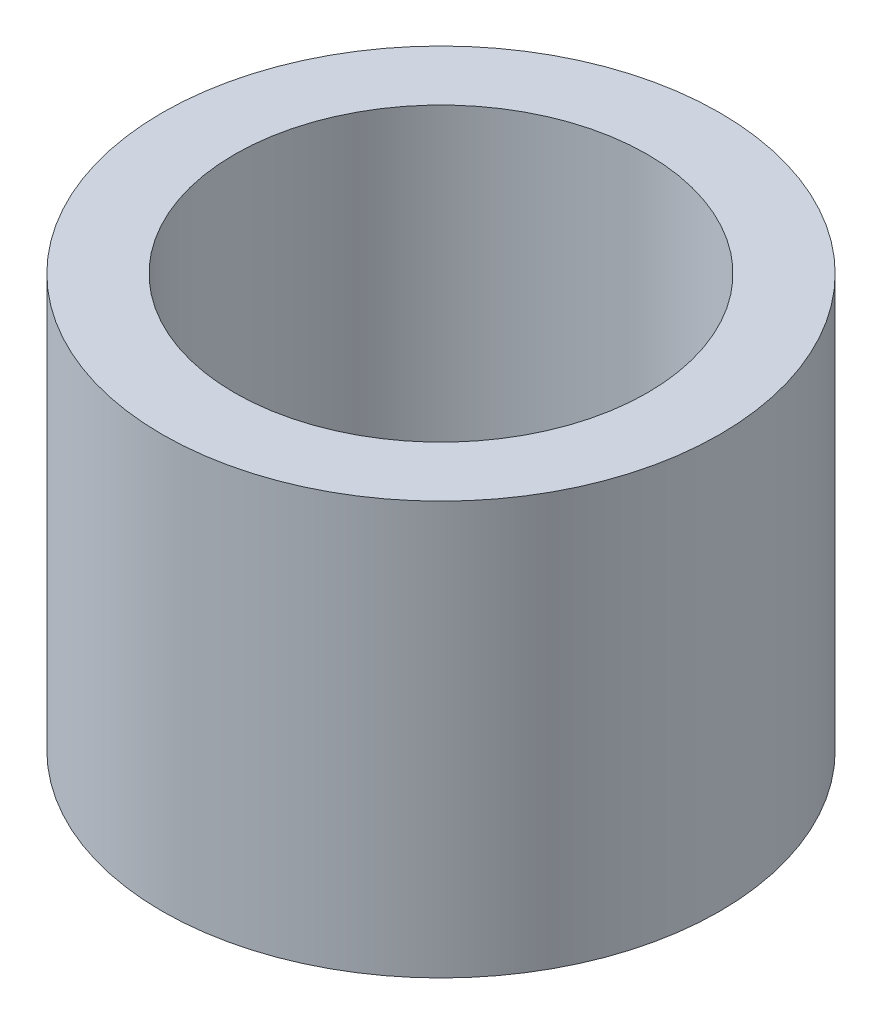
SolidWorks part; units mm, degrees
ref_plane "前视基准面" through (0, 0, 0) normal (0, 0, 1) x (1, 0, 0)
ref_plane "上视基准面" through (0, 0, 0) normal (0, 1, 0) x (1, 0, 0)
ref_plane "右视基准面" through (0, 0, 0) normal (1, 0, 0) x (0, 0, -1)
other "Configuration Table"
sketch "草图1" plane through (0, 0, 0) normal (0, 1, 0) x (1, 0, 0)
  circle A0 centre (0, 0) radius 1.35
  circle A1 centre (0, 0) radius 1
  dimension "D1" = 2.7
  dimension "D2" = 2
extrude "凸台-拉伸1" add sketch "草图1" along normal blind 2
